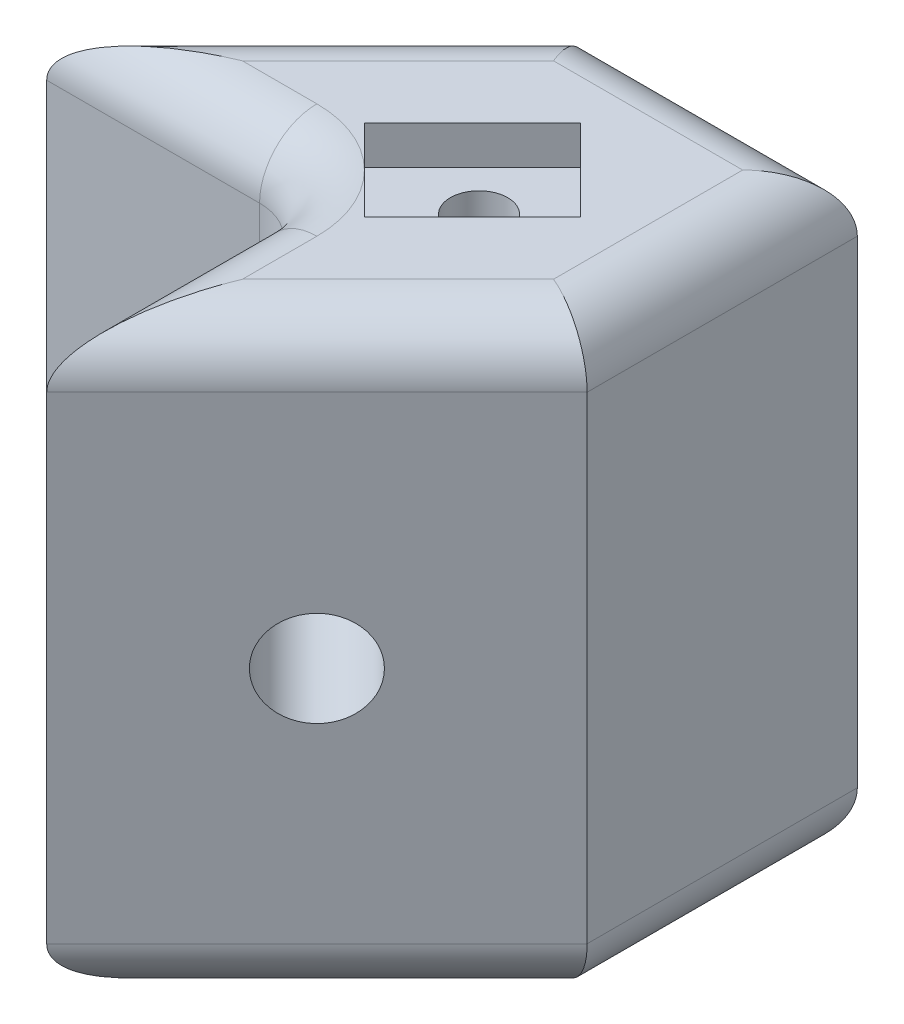
SolidWorks part; units mm, degrees
ref_plane "Front Plane" through (0, 0, 0) normal (0, 0, 1) x (1, 0, 0)
ref_plane "Top Plane" through (0, 0, 0) normal (0, 1, 0) x (1, 0, 0)
ref_plane "Right Plane" through (0, 0, 0) normal (1, 0, 0) x (0, 0, -1)
sketch "Sketch1" plane through (0, 0, 0) normal (0, 1, 0) x (1, 0, 0)
  line L1 (0, 0) -> (-89.8026, 0)
  line L2 (0, 0) -> (0, -89.8026)
  line L3 (-179.6051, -89.8026) -> (-89.8026, -89.8026)
  line L5 (0, -89.8026) -> (-89.8026, -179.6051)
  line L6 (-89.8026, 0) -> (-179.6051, -89.8026)
  line L8 (-89.8026, -89.8026) -> (-89.8026, -179.6051)
  dimension "D1" = 89.8026
  dimension "D2" = 127
extrude "Boss-Extrude3" add sketch "Sketch1" against normal blind 196.85 contours L8 L5 L2 L1 L6 L3
fillet "Fillet3" radius 19.05 13 edges at (-89.8026, -98.425, 89.8026) (-134.7038, -196.85, 44.9013) (-134.7038, -196.85, 89.8026) (-89.8026, -196.85, 134.7038) (-44.9013, -196.85, 134.7038) (0, -196.85, 44.9013) (-44.9013, -196.85, 0) (-134.7038, 0, 44.9013) (-44.9013, 0, 0) (0, 0, 44.9013) (-44.9013, 0, 134.7038) (-89.8026, 0, 134.7038) (-134.7038, 0, 89.8026)
sketch "Sketch5" plane through (44.9013, 0, 44.9013) normal (0.7071, 0, 0.7071) x (0.7071, 0, -0.7071)
  line L0 (-144.5092, 0) -> (-71.3908, 0) construction
  circle A0 centre (-127, -98.552) radius 15.875
  dimension "D3" = 31.75
  dimension "D1" = 63.5
  dimension "D2" = 98.552
extrude "Cut-Extrude1" cut sketch "Sketch5" against normal through all
sketch "Sketch6" plane through (0, 0, 0) normal (0, 1, 0) x (1, 0, 0)
  line L0 (-19.05, -19.05) -> (-81.9118, -81.9118)
  line L1 (-68.4414, -95.3822) -> (-32.5204, -59.4612)
  line L2 (-68.4414, -95.3822) -> (-95.3822, -68.4414)
  line L3 (-32.5204, -59.4612) -> (-59.4612, -32.5204)
  line L4 (-95.3822, -68.4414) -> (-59.4612, -32.5204)
  line L5 (-68.4414, -95.3822) -> (-59.4612, -32.5204) construction
  line L6 (-32.5204, -59.4612) -> (-95.3822, -68.4414) construction
  arc A0 (-70.7526, -108.8526) -> (-108.8526, -70.7526) centre (-108.8526, -108.8526) ccw construction
  circle A1 centre (-62.8618, -62.8618) radius 9.525
  point P7 (-63.9513, -63.9513)
  dimension "D5" = 19.05
  dimension "D1" = 50.8
  dimension "D2" = 38.1
  dimension "D3" = 0
  dimension "D4" = 88.9
extrude "Cut-Extrude4" cut sketch "Sketch6" against normal through all contours A1
sketch "Sketch7" plane through (0, 0, 0) normal (0, 1, 0) x (1, 0, 0)
  line L0 (-19.05, -19.05) -> (-81.9118, -81.9118)
  line L1 (-32.5204, -59.4612) -> (-68.4414, -95.3822)
  line L2 (-32.5204, -59.4612) -> (-59.4612, -32.5204)
  line L3 (-68.4414, -95.3822) -> (-95.3822, -68.4414)
  line L4 (-59.4612, -32.5204) -> (-95.3822, -68.4414)
  line L5 (-32.5204, -59.4612) -> (-95.3822, -68.4414) construction
  line L6 (-68.4414, -95.3822) -> (-59.4612, -32.5204) construction
  arc A0 (-70.7526, -108.8526) -> (-108.8526, -70.7526) centre (-108.8526, -108.8526) ccw construction
  point P6 (0, 0)
  point P7 (-63.9513, -63.9513)
  dimension "D1" = 50.8
  dimension "D2" = 38.1
  dimension "D3" = 0
  dimension "D4" = 0
extrude "Cut-Extrude5" cut sketch "Sketch7" against normal blind 12.7 contours L2 L4 L3 L1
